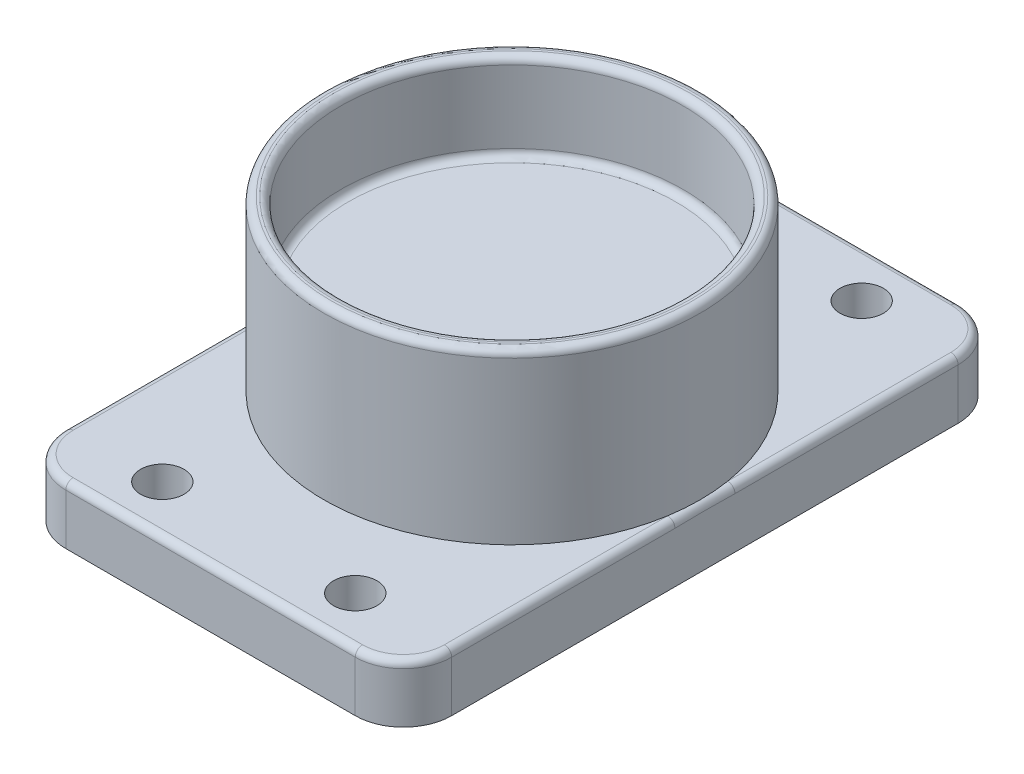
SolidWorks part; units mm, degrees
material "3.3549 (EN-AW 5182)"
ref_plane "Płaszczyzna przednia" through (0, 0, 0) normal (0, 0, 1) x (1, 0, 0)
ref_plane "Płaszczyzna górna" through (0, 0, 0) normal (0, 1, 0) x (1, 0, 0)
ref_plane "Płaszczyzna prawa" through (0, 0, 0) normal (1, 0, 0) x (0, 0, -1)
sketch "Szkic1" plane through (0, 0, 0) normal (0, 1, 0) x (1, 0, 0)
  line L1 (40, -62.5) -> (-40, -62.5)
  line L2 (40, -62.5) -> (40, 62.5)
  line L3 (40, 62.5) -> (-40, 62.5)
  line L4 (-40, -62.5) -> (-40, 62.5)
  line L5 (40, -62.5) -> (-40, 62.5) construction
  line L6 (40, 62.5) -> (-40, -62.5) construction
  point P0 (0, 0)
  dimension "D1" = 125
  dimension "D2" = 80
extrude "Dodanie-wyciągnięcie1" add sketch "Szkic1" along normal blind 12
sketch "Szkic2" plane through (0, 12, 0) normal (0, 1, 0) x (1, 0, 0)
  circle A0 centre (0, 0) radius 39
  circle A1 centre (0, 0) radius 35.5
  dimension "D1" = 78
  dimension "D2" = 3.5
extrude "Dodanie-wyciągnięcie2" add sketch "Szkic2" along normal blind 35
sketch "Szkic4" plane through (0, 12, 0) normal (0, 1, 0) x (1, 0, 0)
  circle A0 centre (0, 0) radius 35.5
  dimension "D1" = 71
extrude "Dodanie-wyciągnięcie3" add sketch "Szkic4" along normal blind 17
fillet "Zaokrąglenie1" radius 10 4 edges at (-40, 6, -62.5) (-40, 6, 62.5) (40, 6, 62.5) (40, 6, -62.5)
fillet "Zaokrąglenie2" radius 1.5 11 edges at (37.0711, 12, -59.5711) (40, 12, 0) (37.0711, 12, 59.5711) (0, 12, 62.5) (-37.0711, 12, 59.5711) (-40, 12, 0) (-37.0711, 12, -59.5711) (0, 29, 35.5) (0, 47, 35.5) (0, 47, 39) (0, 12, -62.5)
sketch "Szkic5" plane through (0, 12, 0) normal (0, 1, 0) x (1, 0, 0)
  line L0 (0, 0) -> (0, -89.9219) construction
  circle A1 centre (-20, -52.5) radius 4
  dimension "D1" = 8
  dimension "D2" = 40
hole_wizard "Otwór pod śrubę M82" positions "Szkic8" profile "Szkic9" hole size "M8" standard "ISO"
sketch "Szkic8" plane through (0, 12, 0) normal (0, 1, 0) x (1, 0, 0)
  point P0 (-20, -52.5)
sketch "Szkic9" plane through (-20, 12, 52.5) normal (1, 0, 0) x (0, 0, 1)
  line L0 (0, 0) -> (0, 18.7039)
  line L1 (0, 18.7039) -> (4.5, 16)
  line L2 (4.5, 16) -> (4.5, 0)
  line L5 (4.5, 0) -> (0, 0)
  line L10 (0, 18.7039) -> (-4.5, 16) construction
  line L11 (0, -6.35) -> (0, 107.95) construction
  dimension "Średnica otworu" = 9
  dimension "Głębokość otworu" = 16
  dimension "Kąt wiertła" = 118
mirror "Lustro3" about plane through (0, 0, 0) normal (1, 0, 0) of "Otwór pod śrubę M82"
mirror "Lustro4" about plane through (0, 0, 0) normal (0, 0, 1) of "Lustro3", "Otwór pod śrubę M82"
